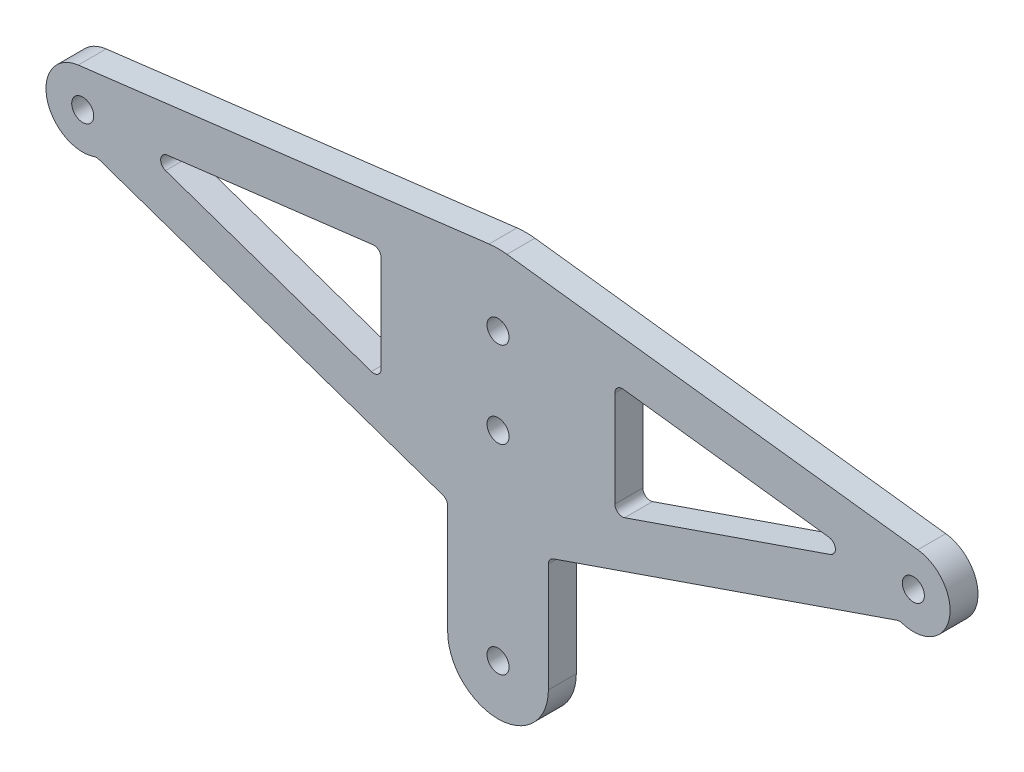
SolidWorks part; units mm, degrees
ref_plane "Plano frontal" through (0, 0, 0) normal (0, 0, 1) x (1, 0, 0)
ref_plane "Plano superior" through (0, 0, 0) normal (0, 1, 0) x (1, 0, 0)
ref_plane "Plano direito" through (0, 0, 0) normal (1, 0, 0) x (0, 0, -1)
sketch "Esboço2" plane through (0, 0, 0) normal (0, 0, 1) x (1, 0, 0)
  line L0 (-1.5, 0) -> (114.5, 0) construction
  line L1 (56.5, 11.9749) -> (56.5, -43.5251) construction
  line L2 (-0.6093, 4.9627) -> (56.5, 11.9749)
  line L3 (113.6093, 4.9627) -> (56.5, 11.9749)
  line L4 (56.5, 11.9749) -> (114.5, 11.9749) construction
  line L5 (49.65, -36.6751) -> (49.65, -21.8451)
  line L6 (63.35, -36.6751) -> (63.35, -21.8451)
  line L7 (64.0237, -20.8999) -> (110.7949, -4.753)
  line L8 (48.9763, -20.8999) -> (2.2051, -4.753)
  line L9 (72.4, 2.8472) -> (72.4, -10.2575)
  line L10 (73.7263, -11.2027) -> (101.727, -1.5361)
  line L11 (101.5225, 0.4017) -> (73.5219, 3.8398)
  line L14 (11.4775, 0.4017) -> (39.4781, 3.8398)
  line L15 (39.2737, -11.2027) -> (11.273, -1.5361)
  line L16 (40.6, 2.8472) -> (40.6, -10.2575)
  circle A0 centre (0, 0) radius 1.5
  circle A1 centre (113, 0) radius 1.5
  circle A2 centre (56.5, 2.1749) radius 1.5
  circle A3 centre (56.5, -9.5251) radius 1.5
  circle A4 centre (56.5, -36.6751) radius 1.5
  arc A5 (49.65, -36.6751) -> (63.35, -36.6751) centre (56.5, -36.6751) ccw
  arc A6 (111.4344, -4.7486) -> (113.6093, 4.9627) centre (113, 0) ccw
  arc A7 (1.5656, -4.7486) -> (-0.6093, 4.9627) centre (0, 0) cw
  arc A8 (64.0237, -20.8999) -> (63.35, -21.8451) centre (64.35, -21.8451) ccw
  arc A9 (49.65, -21.8451) -> (48.9763, -20.8999) centre (48.65, -21.8451) ccw
  arc A10 (2.2051, -4.753) -> (1.5656, -4.7486) centre (1.8788, -5.6983) ccw
  arc A11 (111.4344, -4.7486) -> (110.7949, -4.753) centre (111.1212, -5.6983) ccw
  arc A12 (101.727, -1.5361) -> (101.5225, 0.4017) centre (101.4006, -0.5908) ccw
  arc A13 (72.4, 2.8472) -> (73.5219, 3.8398) centre (73.4, 2.8472) cw
  arc A14 (72.4, -10.2575) -> (73.7263, -11.2027) centre (73.4, -10.2575) ccw
  arc A15 (40.6, 2.8472) -> (39.4781, 3.8398) centre (39.6, 2.8472) ccw
  arc A16 (11.273, -1.5361) -> (11.4775, 0.4017) centre (11.5994, -0.5908) cw
  arc A17 (40.6, -10.2575) -> (39.2737, -11.2027) centre (39.6, -10.2575) cw
  point P11 (1.5, 0)
  point P12 (111.5, 0)
  point P19 (56.5, 0.6749)
  point P22 (56.5, -8.0251)
  point P24 (56.5, 0.6749)
  point P25 (56.5, 3.6749)
  point P26 (56.5, -11.0251)
  point P36 (63.35, -21.1324)
  point P39 (49.65, -21.1324)
  point P41 (1.8697, -4.6372)
  point P44 (111.1303, -4.6372)
  point P66 (86.5556, -13.1212)
  point P67 (103.3171, -2.2358)
  point P68 (9.4097, -2.2358)
  dimension "D1" = 3
  dimension "D5" = 13.7
  dimension "D7" = 10
  dimension "D9" = 1
  dimension "D10" = 1
  dimension "D15" = 1
  dimension "D2" = 110
  dimension "D3" = 8.7
  dimension "D4" = 7
  dimension "D6" = 55.5
  dimension "D8" = 8.3
  dimension "D11" = 49.48
  dimension "D12" = 14.83
  dimension "D13" = 6
  dimension "D14" = 6
  dimension "D16" = 31.8
extrude "Ressalto-extrusão1" add sketch "Esboço2" along normal blind 3.8
fillet "Filete1" radius 10 1 edges at (56.5, 11.9749, 1.9)
